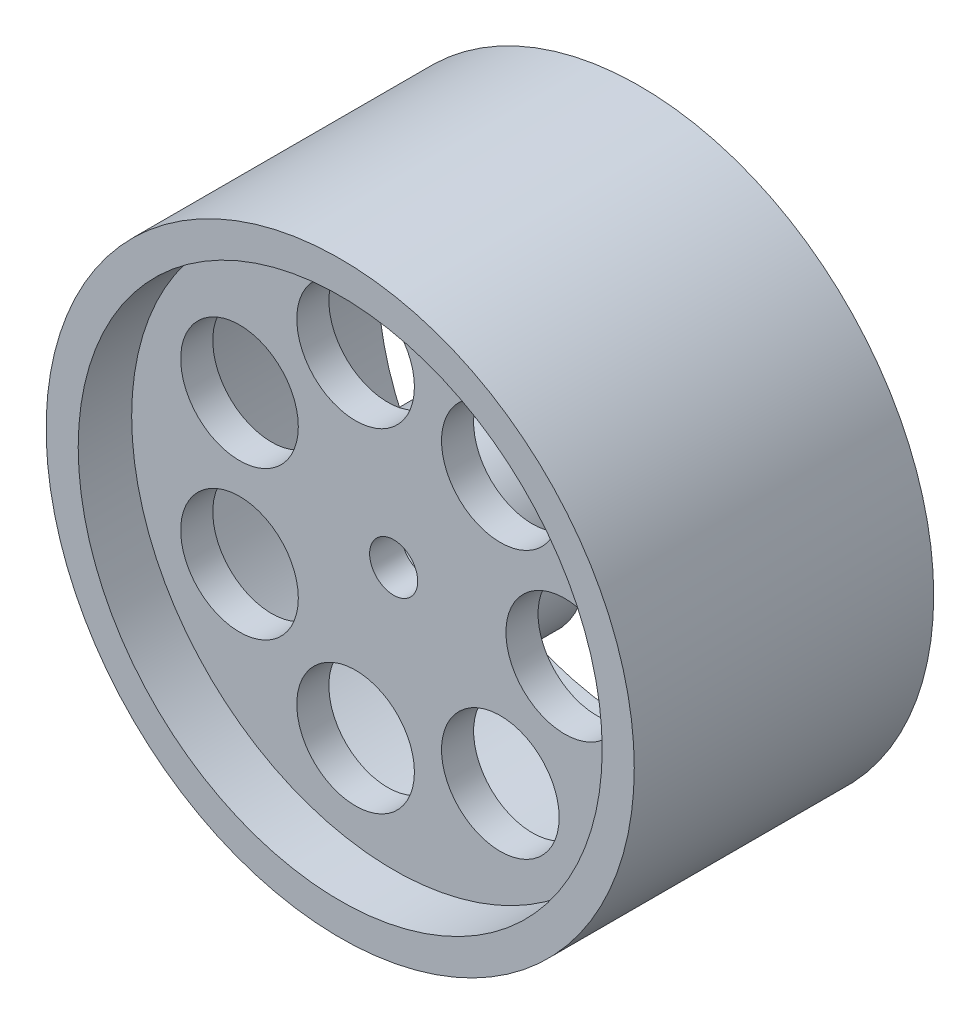
SolidWorks part; units mm, degrees
ref_plane "前视基准面" through (0, 0, 0) normal (0, 0, 1) x (1, 0, 0)
ref_plane "上视基准面" through (0, 0, 0) normal (0, 1, 0) x (1, 0, 0)
ref_plane "右视基准面" through (0, 0, 0) normal (1, 0, 0) x (0, 0, -1)
other "Configuration Table"
sketch "Profile_1" plane through (0, 0, 0) normal (0, 0, 1) x (1, 0, 0)
  circle A0 centre (0, 0) radius 27.5
  circle A1 centre (0, 0) radius 24.5
extrude "Rim_barrel" add sketch "Profile_1" along normal blind 28 from offset 14
sketch "Profile_2" plane through (0, 0, 0) normal (0, 0, 1) x (1, 0, 0)
  circle A0 centre (0, 0) radius 25
  circle A1 centre (0, 0) radius 2.25
  circle A2 centre (16, 0) radius 5.5
  circle A3 centre (9.9758, 12.5093) radius 5.5
  circle A4 centre (-3.5603, 15.5988) radius 5.5
  circle A5 centre (-14.4155, 6.9421) radius 5.5
  circle A6 centre (-14.4155, -6.9421) radius 5.5
  circle A7 centre (-3.5603, -15.5988) radius 5.5
  circle A8 centre (9.9758, -12.5093) radius 5.5
extrude "Spoke_web" add sketch "Profile_2" along normal blind 3 from offset 6
sketch "Profile_3" plane through (0, 0, 0) normal (0, 0, 1) x (1, 0, 0)
  line L0 (6.06, 3.4987) -> (0, 6.9975)
  line L1 (0, 6.9975) -> (-6.06, 3.4987)
  line L2 (-6.06, 3.4987) -> (-6.06, -3.4987)
  line L3 (-6.06, -3.4987) -> (0, -6.9975)
  line L4 (0, -6.9975) -> (6.06, -3.4987)
  line L5 (6.06, -3.4987) -> (6.06, 3.4987)
  circle A0 centre (0, 0) radius 9
extrude "AF12_socket" add sketch "Profile_3" along normal blind 6 from offset 0
